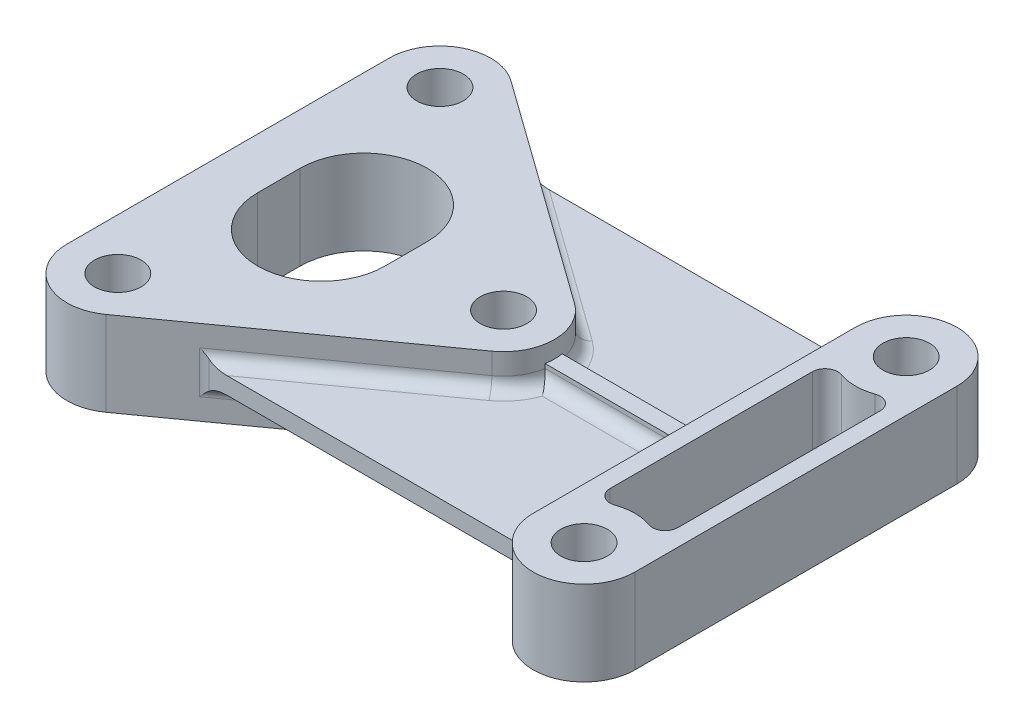
SolidWorks part; units mm, degrees
ref_plane "Front Plane" through (0, 0, 0) normal (0, 0, 1) x (1, 0, 0)
ref_plane "Top Plane" through (0, 0, 0) normal (0, 1, 0) x (1, 0, 0)
ref_plane "Right Plane" through (0, 0, 0) normal (1, 0, 0) x (0, 0, -1)
sketch "Sketch1" plane through (0, 0, 0) normal (0, 1, 0) x (1, 0, 0)
  line L0 (0, 0) -> (0, 68.1704) construction
  line L1 (0, 0) -> (192.6441, 0) construction
  line L2 (0, 38) -> (0, -38)
  line L3 (18.9923, 47.7524) -> (71.9923, 9.7524)
  line L4 (18.9923, -47.7524) -> (71.9923, -9.7524)
  line L5 (122, 38) -> (122, -38) construction
  line L6 (134, 38) -> (134, -38)
  line L7 (110, 38) -> (110, -38)
  line L8 (12, 38) -> (122, 38) construction
  arc A0 (18.9923, 47.7524) -> (0, 38) centre (12, 38) ccw
  arc A1 (0, -38) -> (18.9923, -47.7524) centre (12, -38) ccw
  arc A2 (71.9923, -9.7524) -> (71.9923, 9.7524) centre (65, 0) ccw
  circle A3 centre (12, 38) radius 5.5
  circle A4 centre (12, -38) radius 5.5
  circle A5 centre (65, 0) radius 5.5
  arc A6 (134, 38) -> (110, 38) centre (122, 38) ccw
  arc A7 (110, -38) -> (134, -38) centre (122, -38) ccw
  circle A8 centre (122, 38) radius 5.5
  circle A9 centre (122, -38) radius 5.5
  point P17 (122, 0)
  dimension "D1" = 24
  dimension "D4" = 11
  dimension "D5" = 12
  dimension "D7" = 11
  dimension "D2" = 76
  dimension "D3" = 53
  dimension "D6" = 57
extrude "Boss-Extrude1" add sketch "Sketch1" along normal mid plane 20
sketch "Sketch2" plane through (0, 0, 0) normal (0, 1, 0) x (1, 0, 0)
  line L0 (110, 38) -> (110, -38) construction
  line L1 (18.9923, -47.7524) -> (71.9923, -9.7524) construction
  line L2 (71.9923, 9.7524) -> (18.9923, 47.7524) construction
  line L3 (110, 38) -> (110, -38)
  line L4 (32.5942, -38) -> (71.9923, -9.7524)
  line L5 (71.9923, 9.7524) -> (32.5942, 38)
  line L6 (110, 38) -> (32.5942, 38)
  line L7 (110, -38) -> (32.5942, -38)
  arc A0 (71.9923, -9.7524) -> (71.9923, 9.7524) centre (65, 0) ccw construction
  arc A1 (71.9923, -9.7524) -> (71.9923, 9.7524) centre (65, 0) ccw
extrude "Boss-Extrude2" add sketch "Sketch2" along normal mid plane 4
sketch "Sketch3" plane through (0, 2, 0) normal (0, 1, 0) x (1, 0, 0)
  line L0 (76.8322, 2) -> (110, 2)
  line L1 (65, 0) -> (121.4932, 0) construction
  line L2 (76.8322, -2) -> (110, -2)
  line L3 (110, -38) -> (110, 38) construction
  line L4 (110, -2) -> (110, 2)
  arc A0 (71.9923, -9.7524) -> (71.9923, 9.7524) centre (65, 0) ccw construction
  arc A1 (76.8322, -2) -> (76.8322, 2) centre (65, 0) ccw
  dimension "D1" = 4
extrude "Boss-Extrude3" add sketch "Sketch3" along normal blind 4
sketch "Sketch4" plane through (0, 10, 0) normal (0, 1, 0) x (1, 0, 0)
  line L0 (134, -38) -> (134, 38) construction
  line L2 (114, 29.0557) -> (114, -29.0557)
  line L4 (130, 29.0557) -> (130, -29.0557)
  line L5 (122, 38) -> (122, 7.4249) construction
  line L6 (110, 2) -> (110, 38) construction
  arc A0 (114, 29.0557) -> (130, 29.0557) centre (122, 38) ccw
  arc A1 (130, -29.0557) -> (114, -29.0557) centre (122, -38) ccw
  arc A2 (134, 38) -> (110, 38) centre (122, 38) ccw construction
  arc A3 (110, -38) -> (134, -38) centre (122, -38) ccw construction
  dimension "D1" = 4
  dimension "D2" = 4
extrude "Cut-Extrude1" cut sketch "Sketch4" against normal through all
fillet "Fillet1" radius 3 4 edges at (130, 0, 29.0557) (114, 0, 29.0557) (130, 0, -29.0557) (114, 0, -29.0557)
fillet "Fillet2" radius 3 10 edges at (52.2932, -2, -23.8762) (77, -2, 0) (52.2932, 2, -23.8762) (75.1791, 2, 6.355) (52.2932, -2, 23.8762) (75.1791, 2, -6.355) (32.5942, 0, 38) (52.2932, 2, 23.8762) (93.4161, 2, -2) (93.4161, 2, 2)
sketch "Sketch5" plane through (0, 10, 0) normal (0, 1, 0) x (1, 0, 0)
  line L0 (26.9994, 5) -> (27.0006, -5) construction
  line L1 (41.9994, 5.0019) -> (42.0006, -4.9981)
  line L2 (11.9994, 4.9981) -> (12.0006, -5.0019)
  line L3 (0, 0) -> (27, 0) construction
  line L4 (0, 38) -> (0, -38) construction
  line L5 (65, 0) -> (27, 0) construction
  arc A0 (41.9994, 5.0019) -> (11.9994, 4.9981) centre (26.9994, 5) ccw
  arc A1 (12.0006, -5.0019) -> (42.0006, -4.9981) centre (27.0006, -5) ccw
  point P2 (27, 0)
  point P7 (27, 0)
  point P17 (0, 0)
  point P18 (0, 0)
  point P19 (0, 0)
  dimension "D1" = 15
  dimension "D2" = 10
  dimension "D3" = 38
extrude "Cut-Extrude2" cut sketch "Sketch5" against normal through all
